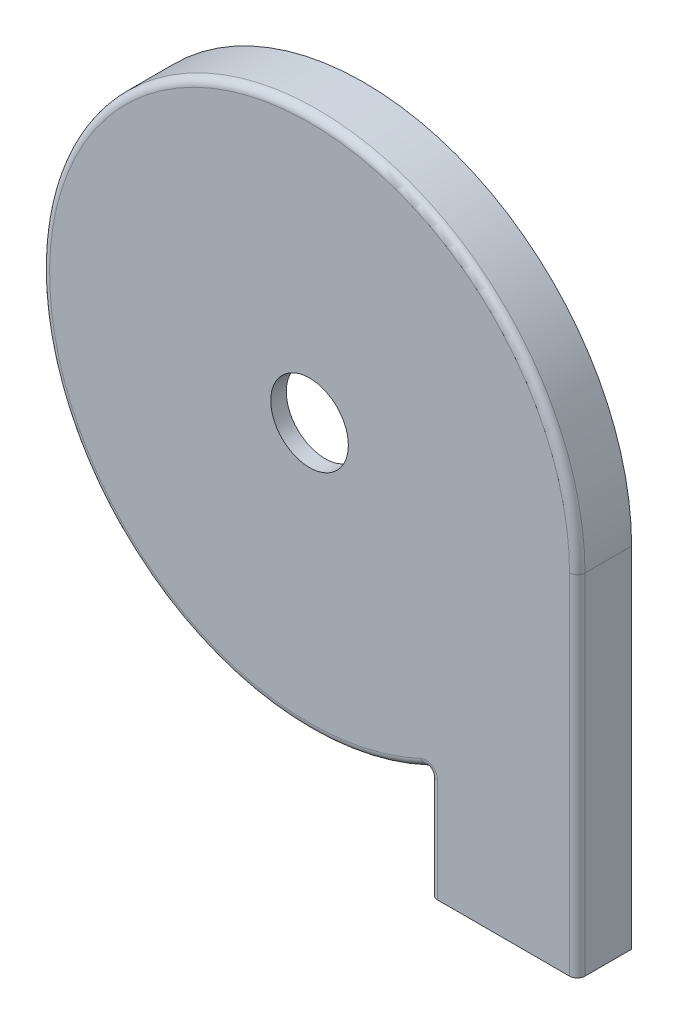
SolidWorks part; units mm, degrees
ref_plane "Plan de face" through (0, 0, 0) normal (0, 0, 1) x (1, 0, 0)
ref_plane "Plan de dessus" through (0, 0, 0) normal (0, 1, 0) x (1, 0, 0)
ref_plane "Plan de droite" through (0, 0, 0) normal (1, 0, 0) x (0, 0, -1)
sketch "Esquisse1" plane through (0, 0, 0) normal (0, 0, 1) x (1, 0, 0)
  line L2 (31.5519, -39.3725) -> (31.5519, 5.6275)
  line L3 (16.5519, -25.9953) -> (16.5519, -39.3725)
  line L6 (16.5519, -39.3725) -> (31.5519, -39.3725)
  arc A2 (31.5519, 5.6275) -> (12.9804, -23.7366) centre (-0.9481, 5.6275) ccw
  arc A3 (16.5519, -25.9953) -> (12.9804, -23.7366) centre (14.0519, -25.9953) ccw
extrude "Boss.-Extru.1" add sketch "Esquisse1" along normal blind 2
sketch "Esquisse2" plane through (0, 0, 2) normal (0, 0, 1) x (1, 0, 0)
  line L0 (14.5519, -41.3725) -> (33.5519, -41.3725)
  line L1 (33.5519, -41.3725) -> (33.5519, 5.6275)
  line L2 (14.5519, -25.9953) -> (14.5519, -41.3725)
  line L3 (16.5519, -39.3725) -> (31.5519, -39.3725)
  line L4 (31.5519, -39.3725) -> (31.5519, 5.6275)
  line L5 (16.5519, -25.9953) -> (16.5519, -39.3725)
  line L6 (16.5519, -39.3725) -> (31.5519, -39.3725)
  line L7 (31.5519, -39.3725) -> (31.5519, 5.6275)
  line L8 (16.5519, -25.9953) -> (16.5519, -39.3725)
  arc A0 (33.5519, 5.6275) -> (13.8376, -25.5436) centre (-0.9481, 5.6275) ccw
  arc A1 (14.5519, -25.9953) -> (13.8376, -25.5436) centre (14.0519, -25.9953) ccw
  arc A2 (31.5519, 5.6275) -> (12.9804, -23.7366) centre (-0.9481, 5.6275) ccw
  arc A3 (16.5519, -25.9953) -> (12.9804, -23.7366) centre (14.0519, -25.9953) ccw
  arc A4 (31.5519, 5.6275) -> (12.9804, -23.7366) centre (-0.9481, 5.6275) ccw
  arc A5 (16.5519, -25.9953) -> (12.9804, -23.7366) centre (14.0519, -25.9953) ccw
  dimension "D1" = 0
  dimension "D2" = 2
extrude "Boss.-Extru.2" add sketch "Esquisse2" against normal blind 5 from offset 2 offset against normal yes
sketch "Esquisse3" plane through (0, 0, -5) normal (0, 0, -1) x (-1, 0, 0)
  line L0 (-31.5519, 5.6275) -> (-29.226, 5.6275)
  line L1 (-12.9804, -23.7366) -> (-12.7662, -23.2848)
  arc A0 (-12.9804, -23.7366) -> (-31.5519, 5.6275) centre (0.9481, 5.6275) ccw construction
  arc A1 (-12.9804, -23.7366) -> (-31.5519, 5.6275) centre (0.9481, 5.6275) ccw
  arc A2 (-12.7662, -23.2848) -> (-31.0519, 5.6275) centre (0.9481, 5.6275) ccw
  arc M5 (-31.5519, 5.6275) -> (-12.9804, -23.7366) centre (0.9481, 5.6275) cw
  dimension "D1" = 0.5
extrude "Boss.-Extru.3" add sketch "Esquisse3" against normal blind 1 from offset 1 contours A2 L1 L0 M5 offset against normal yes
fillet "Congé1" radius 0.25 1 edges at (-27.9931, 22.7322, -4)
sketch "Esquisse4" plane through (0, 0, 0) normal (0, 0, 1) x (1, 0, 0)
  line L3 (14.5519, -25.9953) -> (14.5519, -41.3725)
  line L4 (14.5519, -41.3725) -> (33.5519, -41.3725)
  line L5 (33.5519, -41.3725) -> (33.5519, 5.6275)
  line L6 (14.5519, -25.9953) -> (14.5519, -41.3725)
  line L7 (14.5519, -41.3725) -> (33.5519, -41.3725)
  line L8 (33.5519, -41.3725) -> (33.5519, 5.6275)
  arc A2 (33.5519, 5.6275) -> (13.8376, -25.5436) centre (-0.9481, 5.6275) ccw
  arc A3 (14.5519, -25.9953) -> (13.8376, -25.5436) centre (14.0519, -25.9953) ccw
  arc A4 (33.5519, 5.6275) -> (13.8376, -25.5436) centre (-0.9481, 5.6275) ccw
  arc A5 (14.5519, -25.9953) -> (13.8376, -25.5436) centre (14.0519, -25.9953) ccw
  dimension "D1" = 0
extrude "Boss.-Extru.4" add sketch "Esquisse4" along normal blind 2
fillet "Congé4" radius 1 4 edges at (33.5519, -17.8725, 2) (14.5519, -33.6839, 2) (14.3191, -25.5727, 2) (-30.1059, 24.0685, 2)
sketch "Esquisse5" plane through (0, 0, 2) normal (0, 0, 1) x (1, 0, 0)
  circle A0 centre (-0.9481, 5.6275) radius 5
  dimension "D1" = 10
extrude "Enlèv. mat.-Extru.1" cut sketch "Esquisse5" against normal through all
sketch "Esquisse6" plane through (0, -41.3725, 0) normal (0, -1, 0) x (1, 0, 0)
  line L4 (31.5519, 0) -> (16.5519, 0)
  line L5 (31.5519, -5) -> (31.5519, 0)
  line L6 (16.5519, -5) -> (31.5519, -5)
  line L7 (16.5519, 0) -> (16.5519, -5)
  line L8 (31.5519, 0) -> (16.5519, 0)
  line L9 (31.5519, -5) -> (31.5519, 0)
  line L10 (16.5519, -5) -> (31.5519, -5)
  line L11 (16.5519, 0) -> (16.5519, -5)
  dimension "D1" = 0
extrude "Enlèv. mat.-Extru.2" cut sketch "Esquisse6" against normal blind 2
sketch "Esquisse7" plane through (0, -41.3725, 0) normal (0, -1, 0) x (1, 0, 0)
  line L8 (14.5519, -5) -> (16.5519, -5)
  line L9 (16.5519, -5) -> (16.5519, 0)
  line L10 (16.5519, 0) -> (31.5519, 0)
  line L11 (31.5519, 0) -> (31.5519, -5)
  line L12 (31.5519, -5) -> (33.5519, -5)
  line L13 (33.5519, -5) -> (33.5519, 1)
  line L14 (32.5519, 2) -> (15.5519, 2)
  line L15 (14.5519, 1) -> (14.5519, -5)
  line L16 (14.5519, -5) -> (16.5519, -5)
  line L17 (16.5519, -5) -> (16.5519, 0)
  line L18 (16.5519, 0) -> (31.5519, 0)
  line L19 (31.5519, 0) -> (31.5519, -5)
  line L20 (31.5519, -5) -> (33.5519, -5)
  line L21 (33.5519, -5) -> (33.5519, 1)
  line L22 (32.5519, 2) -> (15.5519, 2)
  line L23 (14.5519, 1) -> (14.5519, -5)
  arc A2 (33.5519, 1) -> (32.5519, 2) centre (32.5519, 1) ccw
  arc A3 (15.5519, 2) -> (14.5519, 1) centre (15.5519, 1) ccw
  arc A4 (33.5519, 1) -> (32.5519, 2) centre (32.5519, 1) ccw
  arc A5 (15.5519, 2) -> (14.5519, 1) centre (15.5519, 1) ccw
  dimension "D1" = 0
extrude "Enlèv. mat.-Extru.3" cut sketch "Esquisse7" against normal blind 2
